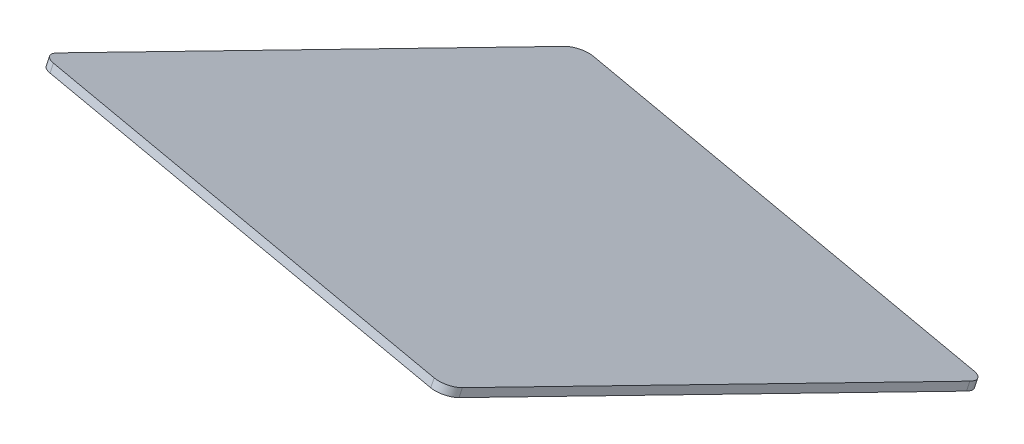
SolidWorks part; units mm, degrees
ref_plane "Front Plane" through (0, 0, 0) normal (0, 0, 1) x (1, 0, 0)
ref_plane "Top Plane" through (0, 0, 0) normal (0, 1, 0) x (1, 0, 0)
ref_plane "Right Plane" through (0, 0, 0) normal (1, 0, 0) x (0, 0, -1)
sketch "Sketch1" plane through (-12.6987, -185.2938, 71.5093) normal (-0.0638, -0.931, 0.3593) x (-0.9979, 0.0638, -0.0119)
  line L4 (339.9646, -133.5065) -> (247.4125, -149.942)
  line L5 (244.9833, -153.4203) -> (261.4187, -245.9723)
  line L6 (264.897, -248.4016) -> (357.4491, -231.9661)
  line L7 (359.8783, -228.4878) -> (343.4429, -135.9358)
  line L8 (339.9646, -133.5065) -> (247.4125, -149.942)
  line L9 (244.9833, -153.4203) -> (261.4187, -245.9723)
  line L10 (264.897, -248.4016) -> (357.4491, -231.9661)
  line L11 (359.8783, -228.4878) -> (343.4429, -135.9358)
  arc A4 (247.4125, -149.942) -> (244.9833, -153.4203) centre (247.9371, -152.8958) ccw
  arc A5 (261.4187, -245.9723) -> (264.897, -248.4016) centre (264.3725, -245.4478) ccw
  arc A6 (357.4491, -231.9661) -> (359.8783, -228.4878) centre (356.9245, -229.0123) ccw
  arc A7 (343.4429, -135.9358) -> (339.9646, -133.5065) centre (340.4891, -136.4603) ccw
  arc A8 (247.4125, -149.942) -> (244.9833, -153.4203) centre (247.9371, -152.8958) ccw
  arc A9 (261.4187, -245.9723) -> (264.897, -248.4016) centre (264.3725, -245.4478) ccw
  arc A10 (357.4491, -231.9661) -> (359.8783, -228.4878) centre (356.9245, -229.0123) ccw
  arc A11 (343.4429, -135.9358) -> (339.9646, -133.5065) centre (340.4891, -136.4603) ccw
  dimension "D1" = 0
extrude "Boss-Extrude1" add sketch "Sketch1" along normal blind 1.6
